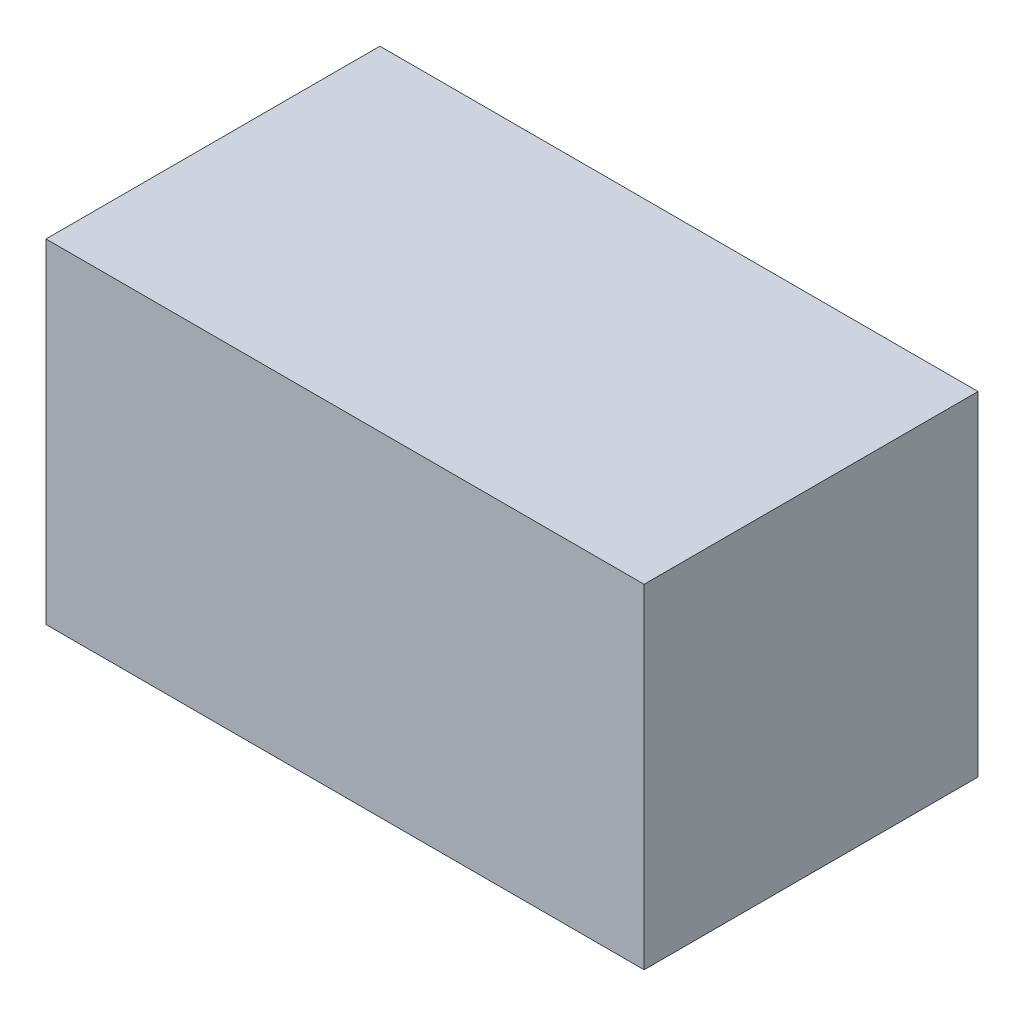
SolidWorks part; units mm, degrees
ref_plane "前视基准面" through (0, 0, 0) normal (0, 0, 1) x (1, 0, 0)
ref_plane "上视基准面" through (0, 0, 0) normal (0, 1, 0) x (1, 0, 0)
ref_plane "右视基准面" through (0, 0, 0) normal (1, 0, 0) x (0, 0, -1)
sketch "草图1" plane through (0, 0, 0) normal (0, 0, 1) x (1, 0, 0)
  line L0 (1.2987, 0.725) -> (1.2987, -0.725)
  line L1 (1.2987, -0.725) -> (-1.2988, -0.725)
  line L2 (-1.2988, -0.725) -> (-1.2988, 0.725)
  line L3 (-1.2988, 0.725) -> (1.2987, 0.725)
extrude "Component_Outline" add sketch "草图1" along normal blind 1.45 separate body
sketch3d "3D草图1"
  line L0 (0, 0, 0) -> (1, 0, 0)
  line L1 (0, 0, 0) -> (0, 1, 0)
  line L2 (0, 0, 0) -> (0, 0, 1)
  point P0 (0, 0, 0)
